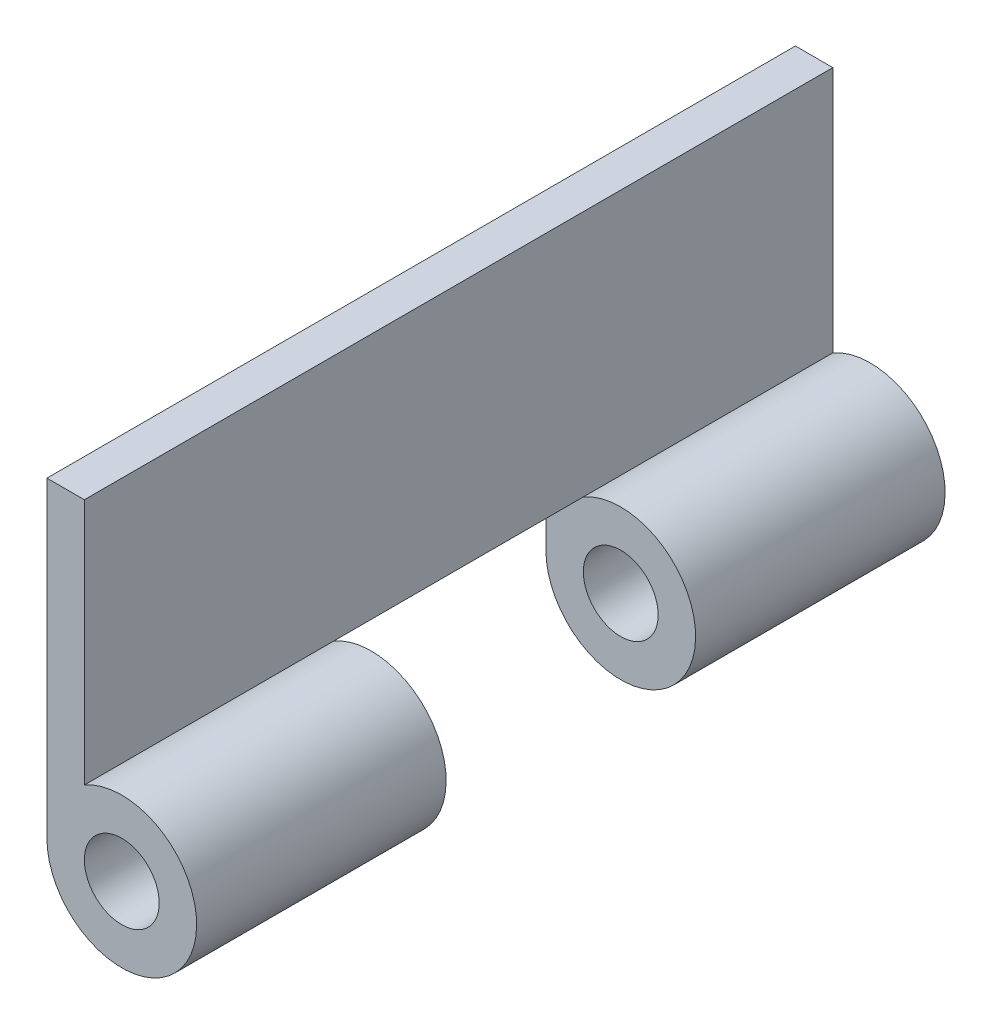
SolidWorks part; units mm, degrees
ref_plane "Front Plane" through (0, 0, 0) normal (0, 0, 1) x (1, 0, 0)
ref_plane "Top Plane" through (0, 0, 0) normal (0, 1, 0) x (1, 0, 0)
ref_plane "Right Plane" through (0, 0, 0) normal (1, 0, 0) x (0, 0, -1)
sketch "Sketch2" plane through (0, 0, 0) normal (0, 0, 1) x (1, 0, 0)
  line L0 (-6, 0) -> (-6, 25)
  line L1 (-6, 25) -> (-3, 25)
  line L2 (-3, 25) -> (-3, 5.1962)
  circle A0 centre (0, 0) radius 3
  arc A1 (-6, 0) -> (-3, 5.1962) centre (0, 0) ccw
  dimension "D1" = 6
  dimension "D2" = 3
  dimension "D3" = 3
  dimension "D4" = 25
extrude "Boss-Extrude1" add sketch "Sketch2" along normal blind 60
ref_plane "Plane1" through (0, 0, 20) normal (0, 0, 1) x (1, 0, 0)
sketch "Sketch3" plane through (0, 0, 20) normal (0, 0, 1) x (1, 0, 0)
  line L0 (-3, 5.1962) -> (-6, 5.1962)
  line L1 (-6, 25) -> (-6, 0) construction
  line L2 (-6, 5.1962) -> (-6, 0)
  arc A0 (-6, 0) -> (-3, 5.1962) centre (0, 0) ccw
  arc A1 (-6, 0) -> (-3, 5.1962) centre (0, 0) ccw construction
extrude "Cut-Extrude1" cut sketch "Sketch3" along normal blind 20
